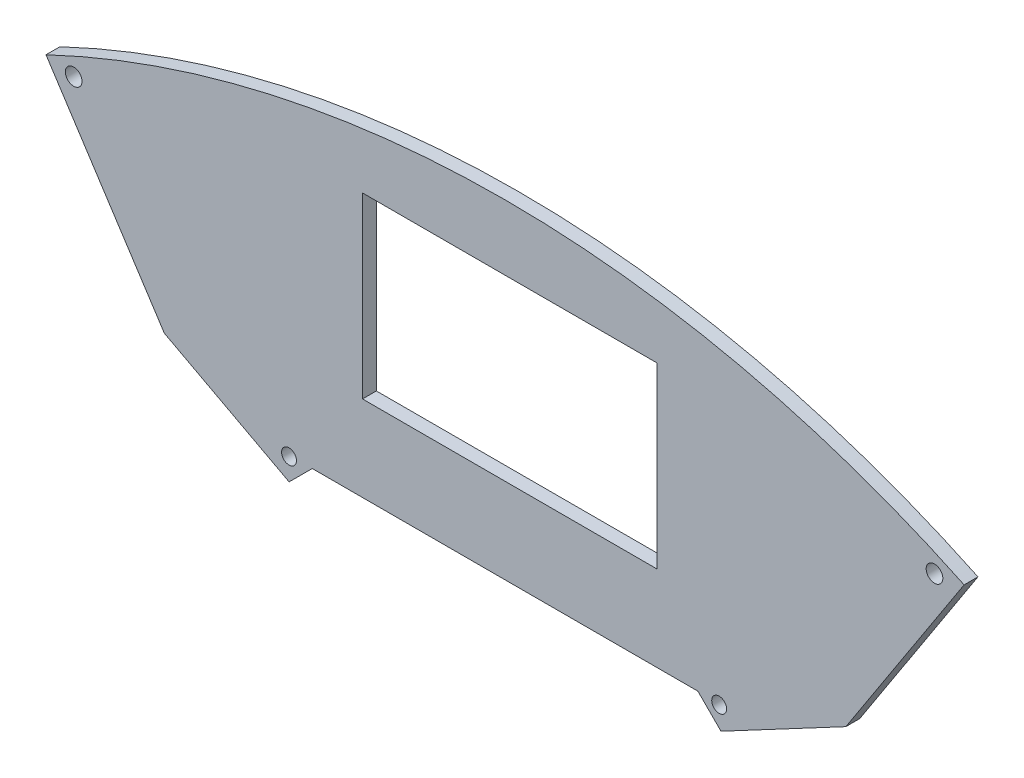
SolidWorks part; units mm, degrees
ref_plane "Front Plane" through (0, 0, 0) normal (0, 0, 1) x (1, 0, 0)
ref_plane "Top Plane" through (0, 0, 0) normal (0, 1, 0) x (1, 0, 0)
ref_plane "Right Plane" through (0, 0, 0) normal (1, 0, 0) x (0, 0, -1)
sketch "Sketch1" plane through (0, 0, 0) normal (0, 0, 1) x (1, 0, 0)
  line L4 (-54.023, -46.7299) -> (-60.7009, -53.4078)
  line L6 (-60.7009, -53.4078) -> (-96.724, -34.2531)
  line L7 (-96.724, -34.2531) -> (-130.873, 18.2701)
  line L8 (99.978, -34.2531) -> (134.127, 18.2701)
  line L14 (63.955, -53.4078) -> (99.978, -34.2531)
  line L15 (57.277, -46.7299) -> (63.955, -53.4078)
  line L16 (-54.023, -46.7299) -> (57.277, -46.7299)
  arc A2 (-130.873, 18.2701) -> (134.127, 18.2701) centre (1.627, -259.3341) cw
sketch "Sketch2" plane through (0, 0, 0) normal (0, 0, 1) x (1, 0, 0)
  line L1 (-39.523, 29.4123) -> (45.477, 29.4123)
  line L2 (-39.523, 29.4123) -> (-39.523, -22.0877)
  line L3 (-39.523, -22.0877) -> (45.477, -22.0877)
  line L4 (45.477, 29.4123) -> (45.477, -22.0877)
  dimension "D1" = 85
  dimension "D2" = 51.5
extrude "Boss-Extrude1" add sketch "Sketch1" along normal blind 4
extrude "Cut-Extrude1" cut sketch "Sketch2" along normal blind 20
sketch "Sketch3" plane through (0, 0, 0) normal (0, 0, 1) x (1, 0, 0)
  circle A0 centre (-122.8819, 16.8045) radius 2.4045
  circle A2 centre (-60.7281, -47.0586) radius 2.15
  circle A3 centre (63.4202, -47.0586) radius 2.15
  circle A4 centre (125.5739, 16.8045) radius 2.4045
  dimension "D2" = 4.3
extrude "Cut-Extrude3" cut sketch "Sketch3" against normal blind 20 from offset 10
